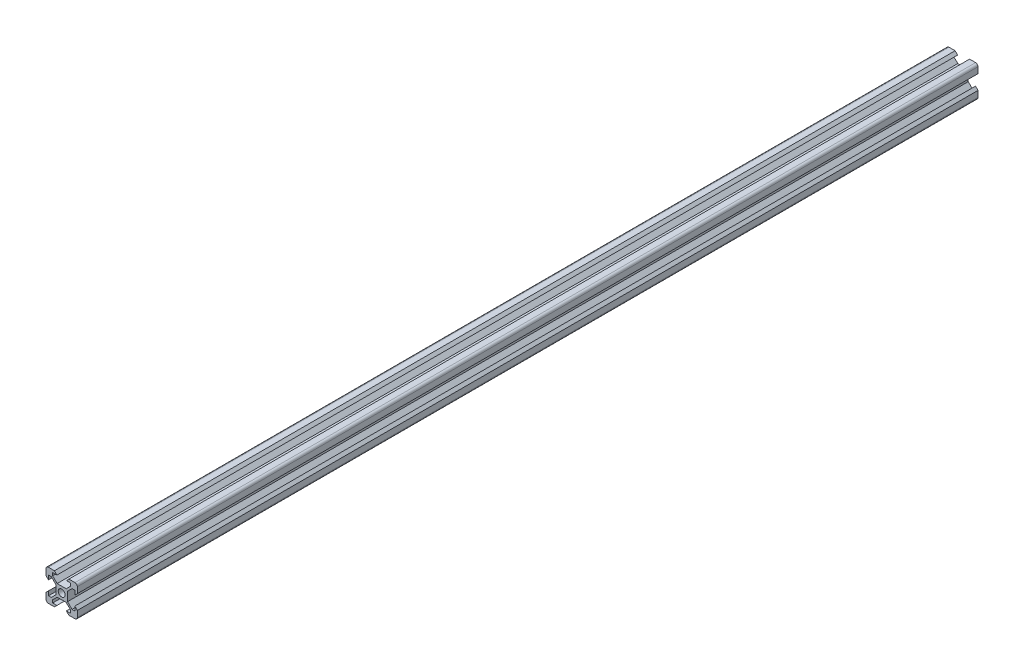
SolidWorks part; units mm, degrees
ref_plane "Front Plane" through (0, 0, 0) normal (0, 0, 1) x (1, 0, 0)
ref_plane "Top Plane" through (0, 0, 0) normal (0, 1, 0) x (1, 0, 0)
ref_plane "Right Plane" through (0, 0, 0) normal (1, 0, 0) x (0, 0, -1)
sketch "Sketch1" plane through (0, 0, 0) normal (0, 0, 1) x (1, 0, 0)
  line L0 (-5.7847, 7.544) -> (-11.512, 13.2713)
  line L1 (-7.544, 7.544) -> (7.544, 7.544)
  line L2 (-7.544, 7.544) -> (-7.544, -7.544)
  line L3 (-7.544, -7.544) -> (7.544, -7.544)
  line L4 (7.544, 7.544) -> (7.544, -7.544)
  line L5 (-7.544, 7.544) -> (7.544, -7.544) construction
  line L6 (-7.544, -7.544) -> (7.544, 7.544) construction
  line L7 (-11.512, 13.2713) -> (-11.512, 16.8)
  line L8 (-11.512, 16.8) -> (-6.052, 16.8)
  line L9 (-6.052, 16.8) -> (-9.252, 20)
  line L10 (-9.252, 20) -> (-17, 20)
  line L11 (-20, 17) -> (-20, 9.252)
  line L12 (-20, 9.252) -> (-16.8, 6.052)
  line L13 (-16.8, 6.052) -> (-16.8, 11.512)
  line L14 (-16.8, 11.512) -> (-13.2713, 11.512)
  line L15 (-13.2713, 11.512) -> (-7.544, 5.7847)
  line L16 (-19.1213, 19.1213) -> (0, 0) construction
  line L17 (13.2713, 11.512) -> (16.8, 11.512)
  line L18 (20, 9.252) -> (20, 17)
  line L19 (17, 20) -> (9.252, 20)
  line L20 (9.252, 20) -> (6.052, 16.8)
  line L21 (6.052, 16.8) -> (11.512, 16.8)
  line L22 (11.512, 16.8) -> (11.512, 13.2713)
  line L23 (11.512, 13.2713) -> (5.7847, 7.544)
  line L24 (7.544, 5.7847) -> (13.2713, 11.512)
  line L25 (16.8, 11.512) -> (16.8, 6.052)
  line L26 (16.8, 6.052) -> (20, 9.252)
  line L27 (19.1213, 19.1213) -> (0, 0) construction
  line L28 (11.512, -13.2713) -> (11.512, -16.8)
  line L29 (9.252, -20) -> (17, -20)
  line L30 (20, -17) -> (20, -9.252)
  line L31 (20, -9.252) -> (16.8, -6.052)
  line L32 (16.8, -6.052) -> (16.8, -11.512)
  line L33 (16.8, -11.512) -> (13.2713, -11.512)
  line L34 (13.2713, -11.512) -> (7.544, -5.7847)
  line L35 (5.7847, -7.544) -> (11.512, -13.2713)
  line L36 (11.512, -16.8) -> (6.052, -16.8)
  line L37 (6.052, -16.8) -> (9.252, -20)
  line L38 (19.1213, -19.1213) -> (0, 0) construction
  line L39 (-13.2713, -11.512) -> (-16.8, -11.512)
  line L40 (-20, -9.252) -> (-20, -17)
  line L41 (-17, -20) -> (-9.252, -20)
  line L42 (-9.252, -20) -> (-6.052, -16.8)
  line L43 (-6.052, -16.8) -> (-11.512, -16.8)
  line L44 (-11.512, -16.8) -> (-11.512, -13.2713)
  line L45 (-11.512, -13.2713) -> (-5.7847, -7.544)
  line L46 (-7.544, -5.7847) -> (-13.2713, -11.512)
  line L47 (-16.8, -11.512) -> (-16.8, -6.052)
  line L48 (-16.8, -6.052) -> (-20, -9.252)
  line L49 (-19.1213, -19.1213) -> (0, 0) construction
  circle A0 centre (0, 0) radius 4.4
  arc A1 (-17, 20) -> (-20, 17) centre (-17, 17) ccw
  arc A2 (20, 17) -> (17, 20) centre (17, 17) ccw
  arc A3 (17, -20) -> (20, -17) centre (17, -17) ccw
  arc A4 (-20, -17) -> (-17, -20) centre (-17, -17) ccw
  point P66 (0, 0)
  dimension "D1" = 8.8
  dimension "D8" = 3
  dimension "D2" = 15.088
  dimension "D3" = 2.488
  dimension "D4" = 8.488
  dimension "D5" = 3.2
  dimension "D6" = 20
  dimension "D7" = 15.2
  dimension "D9" = 4
extrude "Boss-Extrude1" add sketch "Sketch1" along normal mid plane 1150 contours L10 A1 L11 L12 L13 L14 L15 L2 L1 L0 L7 L8 L9 | L18 A2 L19 L20 L21 L22 L23 L1 L4 L24 L17 L25 L26 | L40 A4 L41 L42 L43 L44 L45 L3 L2 L46 L39 L47 L48 | L29 A3 L30 L31 L32 L33 L34 L4 L3 L35 L28 L36 L37 | L4 L1 L2 L3 A0
equation "\"longitud\"= 800"
